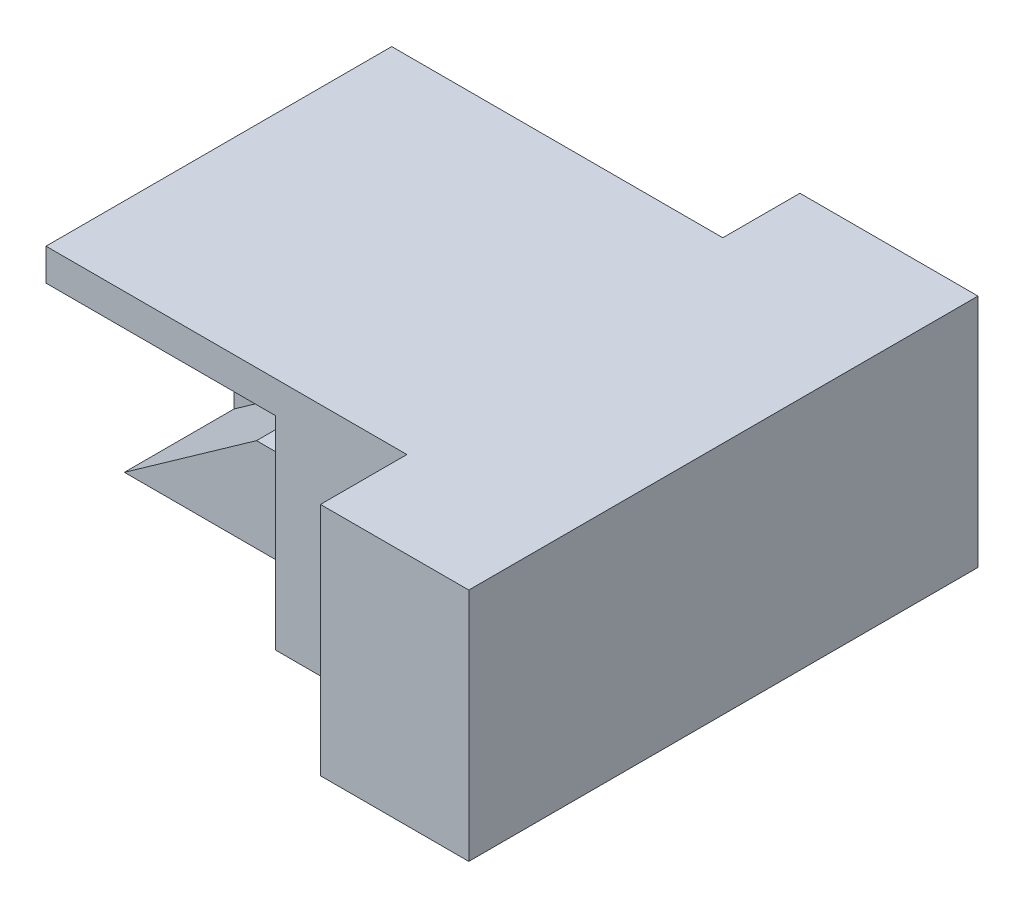
SolidWorks part; units mm, degrees
ref_plane "前视基准面" through (0, 0, 0) normal (0, 0, 1) x (1, 0, 0)
ref_plane "上视基准面" through (0, 0, 0) normal (0, 1, 0) x (1, 0, 0)
ref_plane "右视基准面" through (0, 0, 0) normal (1, 0, 0) x (0, 0, -1)
sketch "草图1" plane through (0, 0, 0) normal (0, 1, 0) x (1, 0, 0)
  line L0 (-37.7179, 18.1881) -> (-37.7179, -25.9404)
  line L1 (-37.7179, -25.9404) -> (8.3486, -25.9404)
  line L2 (8.3486, -25.9404) -> (8.3486, -36.9725)
  line L3 (8.3486, -36.9725) -> (27.2821, -36.9725)
  line L4 (27.2821, -36.9725) -> (27.2821, 28.0275)
  line L5 (27.2821, 28.0275) -> (4.5485, 28.0275)
  line L6 (4.5485, 28.0275) -> (4.5485, 18.1881)
  line L7 (4.5485, 18.1881) -> (-37.7179, 18.1881)
  dimension "D1" = 65
  dimension "D2" = 65
extrude "凸台-拉伸1" add sketch "草图1" along normal blind 30
sketch "草图2" plane through (0, 0, 25.9404) normal (0, 0, 1) x (1, 0, 0)
  line L0 (-37.7179, 25.9124) -> (-8.4116, 25.9124)
  line L1 (-37.7179, 30) -> (-37.7179, 0) construction
  line L2 (-8.4116, 25.9124) -> (-8.4116, 11.9358)
  line L3 (-8.4116, 11.9358) -> (-20.846, 11.9358)
  line L4 (-20.846, 11.9358) -> (-37.7179, 0)
  line L5 (-37.7179, 25.9124) -> (-37.7179, 0)
extrude "切除-拉伸1" cut sketch "草图2" against normal blind 24
sketch "草图3" plane through (0, 0, 25.9404) normal (0, 0, 1) x (1, 0, 0)
  line L1 (-37.7179, 0) -> (-8.4116, 0)
  line L2 (-37.7179, 0) -> (-37.7179, 11.9358)
  line L3 (-37.7179, 11.9358) -> (-8.4116, 11.9358)
  line L4 (-8.4116, 0) -> (-8.4116, 11.9358)
extrude "切除-拉伸2" cut sketch "草图3" against normal blind 10
